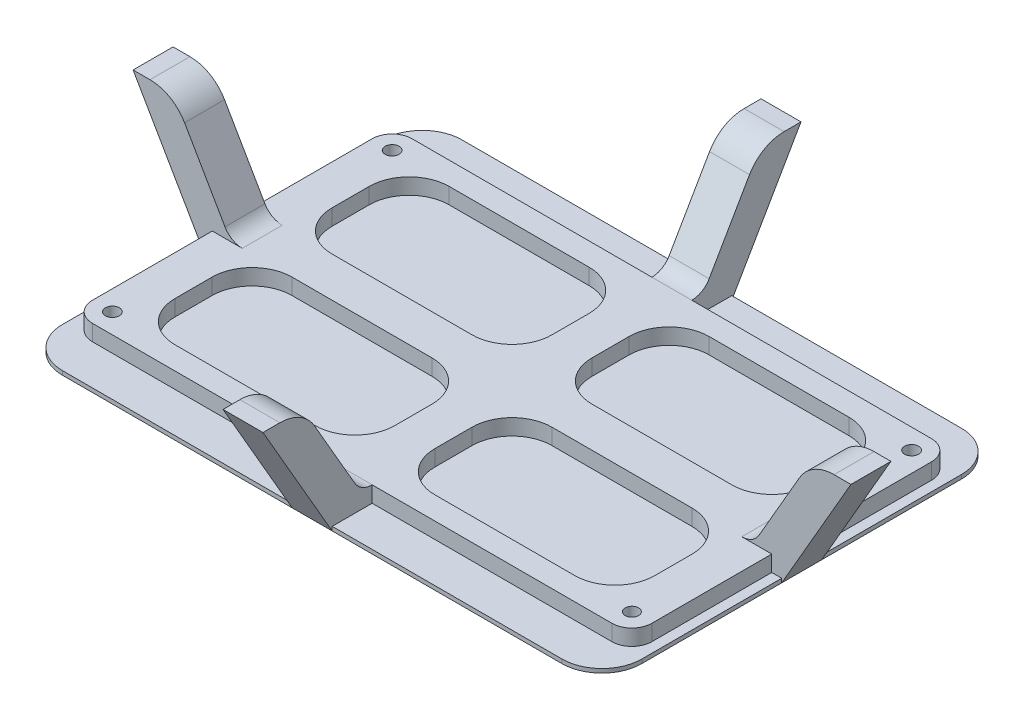
SolidWorks part; units mm, degrees
ref_plane "Спереди" through (0, 0, 0) normal (0, 0, 1) x (1, 0, 0)
ref_plane "Сверху" through (0, 0, 0) normal (0, 1, 0) x (1, 0, 0)
ref_plane "Справа" through (0, 0, 0) normal (1, 0, 0) x (0, 0, -1)
other "Configuration Table"
sketch "Эскиз1" plane through (0, 0, 0) normal (0, 1, 0) x (1, 0, 0)
  line L0 (-1000, 0) -> (49000, 0) construction
  line L1 (-72.5, -50) -> (72.5, -50)
  line L2 (-72.5, -50) -> (-72.5, 50)
  line L3 (-72.5, 50) -> (72.5, 50)
  line L4 (72.5, -50) -> (72.5, 50)
  line L5 (-72.5, -50) -> (72.5, 50) construction
  line L6 (-72.5, 50) -> (72.5, -50) construction
  line L7 (0, -1000) -> (0, 49000) construction
  point P0 (0, 0)
  dimension "D1" = 100
  dimension "D2" = 145
extrude "Бобышка-Вытянуть1" add sketch "Эскиз1" along normal blind 1
sketch "Эскиз2" plane through (0, 1, 0) normal (0, 1, 0) x (1, 0, 0)
  line L0 (-1000, 0) -> (49000, 0) construction
  line L1 (0, -1000) -> (0, 49000) construction
  line L2 (72.5, 50) -> (-72.5, 50) construction
  line L3 (-70, -40) -> (70, -40)
  line L4 (-70, -40) -> (-70, 40)
  line L5 (-70, 40) -> (70, 40)
  line L6 (70, -40) -> (70, 40)
  line L7 (-70, -40) -> (70, 40) construction
  line L8 (-70, 40) -> (70, -40) construction
  line L9 (-60.0474, -34.3128) -> (60.0474, -34.3128)
  line L10 (-60.0474, -34.3128) -> (-60.0474, 34.3128)
  line L11 (-60.0474, 34.3128) -> (60.0474, 34.3128)
  line L12 (60.0474, -34.3128) -> (60.0474, 34.3128)
  line L13 (-60.0474, -34.3128) -> (60.0474, 34.3128) construction
  line L14 (-60.0474, 34.3128) -> (60.0474, -34.3128) construction
  line L15 (-60.0474, -5) -> (60.0474, -5)
  line L16 (-60.0474, -5) -> (-60.0474, 5)
  line L17 (-60.0474, 5) -> (60.0474, 5)
  line L18 (60.0474, -5) -> (60.0474, 5)
  line L19 (-60.0474, -5) -> (60.0474, 5) construction
  line L20 (-60.0474, 5) -> (60.0474, -5) construction
  line L21 (-5, -50) -> (5, -50)
  line L22 (-5, -50) -> (-5, 50)
  line L23 (-5, 50) -> (5, 50)
  line L24 (5, -50) -> (5, 50)
  line L25 (-5, -50) -> (5, 50) construction
  line L26 (-5, 50) -> (5, -50) construction
  circle A0 centre (65, 35) radius 5
  circle A1 centre (-65, 35) radius 5
  circle A2 centre (65, -35) radius 5
  circle A3 centre (-65, -35) radius 5
  point P13 (0, 0)
  point P18 (0, 0)
  point P19 (0, 0)
  point P28 (0, 0)
  dimension "D1" = 10
  dimension "D2" = 130
  dimension "D3" = 70
  dimension "D4" = 10
  dimension "D5" = 10
extrude "Бобышка-Вытянуть2" add sketch "Эскиз2" along normal blind 4 contours A3 L10 A1 L4 | A3 L3 L22 L9 | A3 | L3 A2 L9 L24 | L12 A2 L6 A0 | A2 | A0 | A0 L5 L24 L11 | L5 A1 L11 L22 | A1 L10 | L16 L15 L18 L17
sketch "Эскиз3" plane through (0, 5, 0) normal (0, 1, 0) x (1, 0, 0)
  line L4 (-60.0474, -5) -> (60.0474, -5)
  line L5 (60.0474, -5) -> (60.0474, 5)
  line L6 (60.0474, -5) -> (60.0474, 5)
  line L7 (60.0474, 5) -> (-60.0474, 5)
  line L8 (-60.0474, -5) -> (60.0474, -5)
  line L12 (-60.0474, -34.3128) -> (60.0474, -34.3128)
  line L13 (60.0474, 5) -> (-60.0474, 5)
  line L14 (-60.0474, 5) -> (-60.0474, -5)
  line L15 (-60.0474, 5) -> (-60.0474, -5)
  line L16 (-60.0474, -34.3128) -> (60.0474, -34.3128)
  line L20 (-70, -40) -> (70, -40)
  line L21 (-70, 40) -> (-70, -40)
  line L22 (70, 40) -> (-70, 40)
  line L23 (70, -40) -> (70, 40)
  line L24 (-70, -40) -> (70, -40)
  line L25 (-70, 40) -> (-70, -40)
  line L26 (70, 40) -> (-70, 40)
  line L27 (70, -40) -> (70, 40)
  line L28 (60.0474, -34.3128) -> (60.0474, 34.3128)
  line L29 (60.0474, -34.3128) -> (60.0474, 34.3128)
  line L30 (60.0474, 34.3128) -> (-60.0474, 34.3128)
  line L31 (60.0474, 34.3128) -> (-60.0474, 34.3128)
  line L32 (-60.0474, 34.3128) -> (-60.0474, -34.3128)
  line L33 (-60.0474, 34.3128) -> (-60.0474, -34.3128)
  circle A0 centre (-65, 35) radius 1.75
  circle A1 centre (-65, -35) radius 5
  circle A2 centre (-65, -35) radius 5
  circle A3 centre (65, -35) radius 5
  circle A4 centre (65, -35) radius 5
  circle A5 centre (-65, 35) radius 5
  circle A6 centre (-65, 35) radius 5
  circle A7 centre (65, 35) radius 5
  circle A8 centre (65, 35) radius 5
  circle A9 centre (65, 35) radius 1.75
  circle A10 centre (-65, -35) radius 1.75
  circle A11 centre (65, -35) radius 1.6823
  dimension "D8" = 3.5
  dimension "D1" = 0
  dimension "D2" = 0
  dimension "D3" = 0
  dimension "D4" = 0
  dimension "D5" = 0
  dimension "D6" = 0
  dimension "D7" = 0
extrude "Вырез-Вытянуть1" cut sketch "Эскиз3" against normal through all contours A0 | A10 | A11 | A9
sketch "Эскиз4" plane through (0, 0, 0) normal (0, 0, 1) x (1, 0, 0)
  line L0 (-62.5, 0) -> (-79.8205, 30)
  line L1 (-65, 1) -> (-70, 1) construction
  line L2 (-70, 1) -> (-70, 5) construction
  line L3 (-65, 5) -> (-70, 5) construction
  line L5 (-5, 1) -> (-5, 5)
  line L13 (72.5, 0) -> (-72.5, 0) construction
  line L14 (-72.5, 0) -> (-72.5, 1) construction
  line L16 (72.5, 1) -> (72.5, 0) construction
  line L17 (-65, 1) -> (-70, 1)
  line L18 (-70, 1) -> (-70, 5)
  line L19 (-65, 5) -> (-70, 5)
  line L21 (72.5, 0) -> (-72.5, 0)
  line L22 (-72.5, 0) -> (-72.5, 1)
  line L24 (72.5, 1) -> (72.5, 0)
  line L25 (-72.5, 0) -> (-89.8205, 30)
  line L26 (-89.8205, 30) -> (-79.8205, 30)
  line L27 (0, -1000) -> (0, 49000) construction
  line L28 (-72.5, 0) -> (-63.0774, 0)
  line L30 (72.5, 0) -> (63.0774, 0)
  line L31 (72.5, 0) -> (89.8205, 30)
  line L32 (89.8205, 30) -> (79.8205, 30)
  line L33 (62.5, 0) -> (79.8205, 30)
  line L34 (63.0774, 0) -> (62.5, 0)
  line L35 (-1000, 0) -> (49000, 0) construction
  line L40 (-5, 1) -> (-5, 5)
  line L43 (-65, 5) -> (-70, 1)
  line L46 (-65, 5) -> (-70, 1)
  line L48 (-70, 1) -> (-5, 1)
  line L49 (-5, 5) -> (-65, 5)
  line L50 (-5, 5) -> (-65, 5)
  line L51 (-70, 1) -> (-5, 1)
  point P2 (-62.5, 0)
  point P3 (-93.6739, 30)
  dimension "D1" = 0
  dimension "D2" = 60
  dimension "D3" = 30
  dimension "D4" = 10
extrude "Бобышка-Вытянуть3" add sketch "Эскиз4" along normal blind 5 and the other way blind 5
sketch "Эскиз5" plane through (0, 0, 0) normal (1, 0, 0) x (0, 0, -1)
  line L0 (-50, 1) -> (-5, 1) construction
  line L1 (-5, 1) -> (-5, 0) construction
  line L2 (-5, 0) -> (-50, 0) construction
  line L3 (-50, 0) -> (-50, 1) construction
  line L4 (-35, 1) -> (-40, 1) construction
  line L5 (-40, 1) -> (-40, 5) construction
  line L6 (-35, 5) -> (-40, 5) construction
  line L7 (-5, 5) -> (-5, 1) construction
  line L8 (-5, 1) -> (-35, 1) construction
  line L9 (-35, 5) -> (-5, 5) construction
  line L10 (-50, 1) -> (-5, 1)
  line L11 (-5, 1) -> (-5, 0)
  line L12 (-5, 0) -> (-50, 0)
  line L13 (-50, 0) -> (-50, 1)
  line L14 (-35, 1) -> (-40, 1)
  line L15 (-40, 1) -> (-40, 5)
  line L16 (-35, 5) -> (-40, 5)
  line L17 (-5, 5) -> (-5, 1)
  line L18 (-5, 1) -> (-35, 1)
  line L19 (-35, 5) -> (-5, 5)
  line L20 (-50, 0) -> (-67.3205, 30)
  line L21 (-67.3205, 30) -> (-57.3205, 30)
  line L22 (-57.3205, 30) -> (-40, 0)
  line L23 (0, -1000) -> (0, 49000) construction
  line L24 (-50, 0) -> (-40, 0)
  line L25 (50, 0) -> (67.3205, 30)
  line L26 (67.3205, 30) -> (57.3205, 30)
  line L27 (57.3205, 30) -> (40, 0)
  line L28 (50, 0) -> (40, 0)
  dimension "D1" = 10
  dimension "D2" = 30
  dimension "D3" = 60
extrude "Бобышка-Вытянуть4" add sketch "Эскиз5" along normal blind 5 and the other way blind 5 contours L22 L21 L20 L13 L10 | L28 L25 L26 L27
fillet "Скругление1" radius 10 4 edges at (72.5, 0.5, 50) (72.5, 0.5, -50) (-72.5, 0.5, -50) (-72.5, 0.5, 50)
fillet "Скругление3" radius 10 16 edges at (-60.0474, 3, 5) (-60.0474, 3, 34.3128) (-5, 3, 34.3128) (-5, 3, 5) (-60.0474, 3, -5) (-5, 3, -34.3128) (-5, 3, -5) (60.0474, 3, -5) (60.0474, 3, -34.3128) (5, 3, 5) (60.0474, 3, 5) (60.0474, 3, 34.3128) (5, 3, 34.3128) (5, 3, -5) (5, 3, -34.3128) (-60.0474, 3, -34.3128)
fillet "Скругление4" radius 5 4 edges at (0, 5, 42.8868) (-65.3868, 5, 0) (65.3868, 5, 0) (0, 5, -42.8868)
fillet "Скругление5" radius 10 4 edges at (-79.8205, 30, 0) (0, 30, 57.3205) (79.8205, 30, 0) (0, 30, -57.3205)
